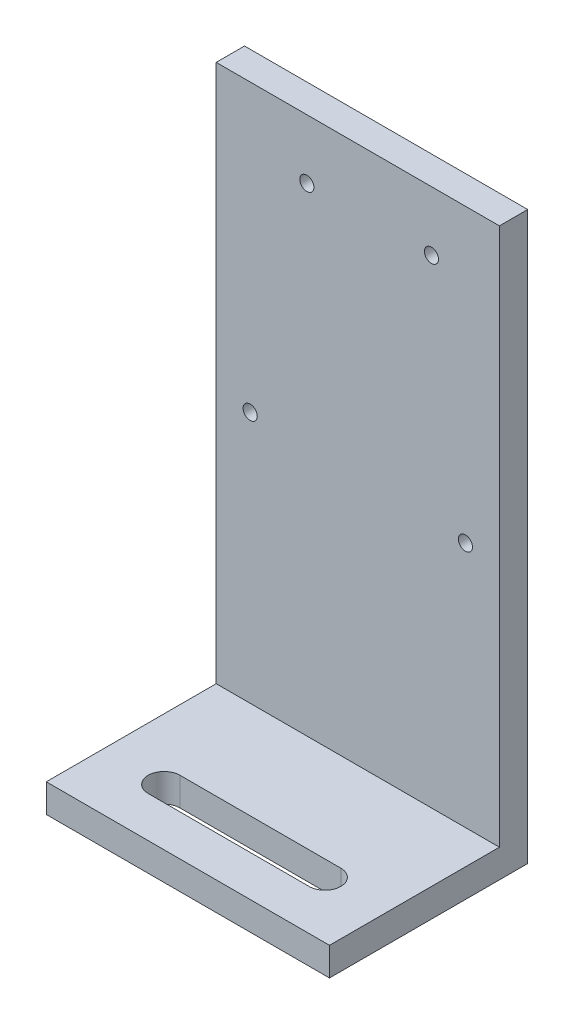
SolidWorks part; units mm, degrees
ref_plane "Front Plane" through (0, 0, 0) normal (0, 0, 1) x (1, 0, 0)
ref_plane "Top Plane" through (0, 0, 0) normal (0, 1, 0) x (1, 0, 0)
ref_plane "Right Plane" through (0, 0, 0) normal (1, 0, 0) x (0, 0, -1)
sketch "Sketch1" plane through (0, 0, 0) normal (0, 0, 1) x (1, 0, 0)
  line L1 (0, 0) -> (63.5, 0)
  line L2 (0, 0) -> (0, 127)
  line L3 (0, 127) -> (63.5, 127)
  line L4 (63.5, 0) -> (63.5, 127)
  dimension "D1" = 127
  dimension "D2" = 63.5
extrude "Boss-Extrude1" add sketch "Sketch1" along normal blind 6.35 contours L3 L4 L1 L2
sketch "Sketch2" plane through (0, 0, 6.35) normal (0, 0, 1) x (1, 0, 0)
  line L0 (0, 104.775) -> (63.5, 104.775) construction
  line L1 (0, 0) -> (0, 127) construction
  line L2 (63.5, 0) -> (63.5, 127) construction
  line L3 (0, 0) -> (63.5, 0) construction
  line L4 (0, 61.595) -> (63.5, 61.595) construction
  line L5 (0, 62.865) -> (63.5, 62.865) construction
  line L6 (0, 113.665) -> (63.5, 113.665) construction
  circle A0 centre (55.88, 61.595) radius 1.5875
  circle A1 centre (7.62, 62.865) radius 1.5875
  circle A2 centre (20.32, 113.665) radius 1.5875
  circle A3 centre (48.26, 113.665) radius 1.5875
  point P22 (0, 0)
  point P23 (0, 0)
  dimension "D3" = 3.175
  dimension "D7" = 3.175
  dimension "D9" = 3.175
  dimension "D11" = 3.175
  dimension "D1" = 104.775
  dimension "D2" = 43.18
  dimension "D4" = 7.62
  dimension "D5" = 1.27
  dimension "D6" = 50.8
  dimension "D8" = 7.62
  dimension "D10" = 20.32
  dimension "D12" = 27.94
extrude "Cut-Extrude1" cut sketch "Sketch2" against normal through all
sketch "Sketch3" plane through (0, 0, 6.35) normal (0, 0, 1) x (1, 0, 0)
  line L0 (63.5, 0) -> (63.5, 127) construction
  line L1 (0, 0) -> (63.5, 0)
  line L2 (0, 0) -> (0, 6.35)
  line L3 (0, 6.35) -> (63.5, 6.35)
  line L4 (63.5, 0) -> (63.5, 6.35)
  dimension "D1" = 6.35
extrude "Boss-Extrude2" add sketch "Sketch3" along normal blind 38.1
sketch "Sketch4" plane through (0, 6.35, 0) normal (0, 1, 0) x (1, 0, 0)
  line L0 (0, -44.45) -> (0, -6.35) construction
  line L2 (13.716, -28.194) -> (49.784, -28.194)
  line L3 (13.716, -35.306) -> (49.784, -35.306)
  line L4 (63.5, -44.45) -> (0, -44.45) construction
  arc A0 (13.716, -28.194) -> (13.716, -35.306) centre (13.716, -31.75) ccw
  arc A1 (49.784, -35.306) -> (49.784, -28.194) centre (49.784, -31.75) ccw
  point P10 (13.716, -31.75)
  point P11 (13.716, -31.75)
  dimension "D1" = 7.112
  dimension "D2" = 7.112
  dimension "D3" = 36.068
  dimension "D4" = 13.716
  dimension "D5" = 12.7
extrude "Cut-Extrude2" cut sketch "Sketch4" against normal through all contours A0 L3 A1 L2
